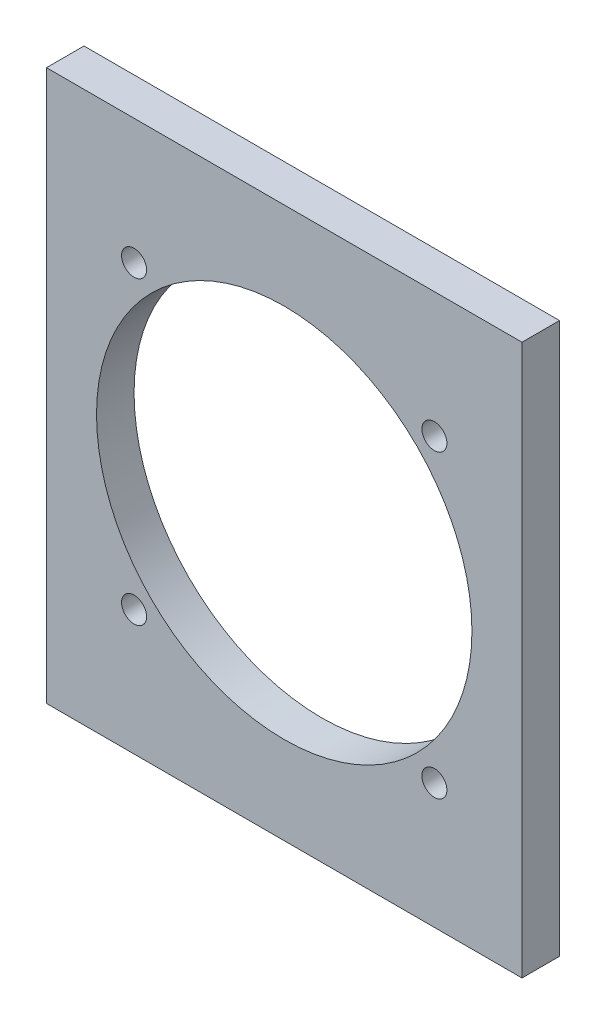
SolidWorks part; units mm, degrees
ref_plane "Ön Düzlem" through (0, 0, 0) normal (0, 0, 1) x (1, 0, 0)
ref_plane "Üst Düzlem" through (0, 0, 0) normal (0, 1, 0) x (1, 0, 0)
ref_plane "Sağ Düzlem" through (0, 0, 0) normal (1, 0, 0) x (0, 0, -1)
sketch "Sketch1" plane through (0, 0, 0) normal (0, 0, 1) x (1, 0, 0)
  line L1 (-95, -110) -> (95, -110)
  line L2 (-95, -110) -> (-95, 110)
  line L3 (-95, 110) -> (95, 110)
  line L4 (95, -110) -> (95, 110)
  line L5 (-95, -110) -> (95, 110) construction
  line L6 (-95, 110) -> (95, -110) construction
  point P0 (0, 0)
  dimension "D1" = 220
  dimension "D2" = 190
extrude "Boss-Extrude1" add sketch "Sketch1" along normal blind 15
sketch "Sketch2" plane through (0, 0, 15) normal (0, 0, 1) x (1, 0, 0)
  line L1 (-60, -60) -> (60, -60) construction
  line L2 (-60, -60) -> (-60, 60) construction
  line L3 (-60, 60) -> (60, 60) construction
  line L4 (60, -60) -> (60, 60) construction
  line L5 (-60, -60) -> (60, 60) construction
  line L6 (-60, 60) -> (60, -60) construction
  circle A4 centre (0, 0) radius 75
  circle A5 centre (-60, 60) radius 5
  circle A6 centre (60, 60) radius 5
  circle A7 centre (60, -60) radius 5
  circle A8 centre (-60, -60) radius 5
  dimension "D1" = 150
  dimension "D3" = 10
  dimension "D2" = 120
extrude "Cut-Extrude1" cut sketch "Sketch2" against normal up to surface (15 mm away) up to face at (0, 0, 0)
